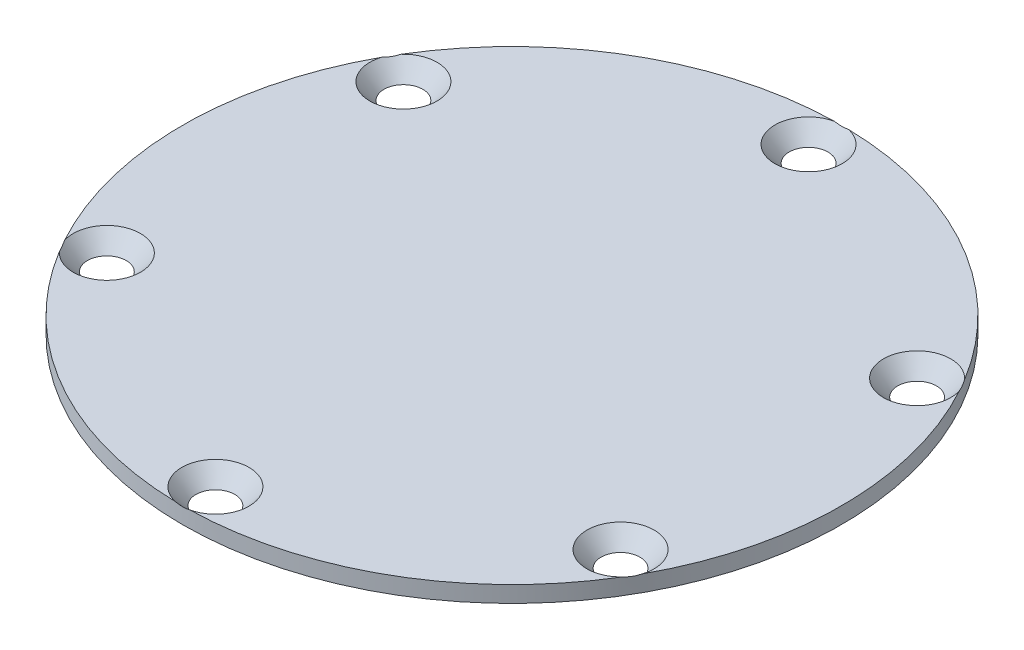
SolidWorks part; units mm, degrees
material "6061-T6 (SS)"
ref_plane "Front Plane" through (0, 0, 0) normal (0, 0, 1) x (1, 0, 0)
ref_plane "Top Plane" through (0, 0, 0) normal (0, 1, 0) x (1, 0, 0)
ref_plane "Right Plane" through (0, 0, 0) normal (1, 0, 0) x (0, 0, -1)
sketch "Sketch1" plane through (0, 0, 0) normal (0, 1, 0) x (1, 0, 0)
  circle A0 centre (0, 0) radius 31.75
  dimension "D1" = 63.5
extrude "Boss-Extrude1" add sketch "Sketch1" along normal blind 1.5748
hole_wizard "CSK for #4 Flat Head Socket Cap Screw1" positions "Sketch3" profile "Sketch2" countersink size "#4" standard "Ansi Inch" end condition through all
sketch "Sketch3" plane through (0, 1.5748, 0) normal (0, 1, 0) x (-1, 0, 0)
  point P0 (0, 28.575)
  point P13 (24.7467, 14.2875)
  point P14 (24.7467, -14.2875)
  point P15 (0, -28.575)
  point P16 (-24.7467, -14.2875)
  point P17 (-24.7467, 14.2875)
  dimension "D1" = 28.575
  dimension "D2" = 6
sketch "Sketch2" plane through (0, 1.5748, 28.575) normal (1, 0, 0) x (0, 0, 1)
  line L0 (0, 0) -> (0, 1.5748)
  line L1 (0, 1.5748) -> (1.632, 1.5748)
  line L2 (1.632, 1.5748) -> (1.6319, 1.8481)
  line L3 (1.6319, 1.8481) -> (3.2385, 0)
  line L5 (3.2385, 0) -> (0, 0)
  line L6 (-1.6319, 1.8481) -> (-3.2385, 0) construction
  line L11 (0, -6.35) -> (0, 107.95) construction
  dimension "Thru Hole Dia." = 3.2639
  dimension "Thru Hole Depth" = 1.5748
  dimension "Near C'Sink Dia." = 6.477
  dimension "Near C'Sink Angle" = 82
